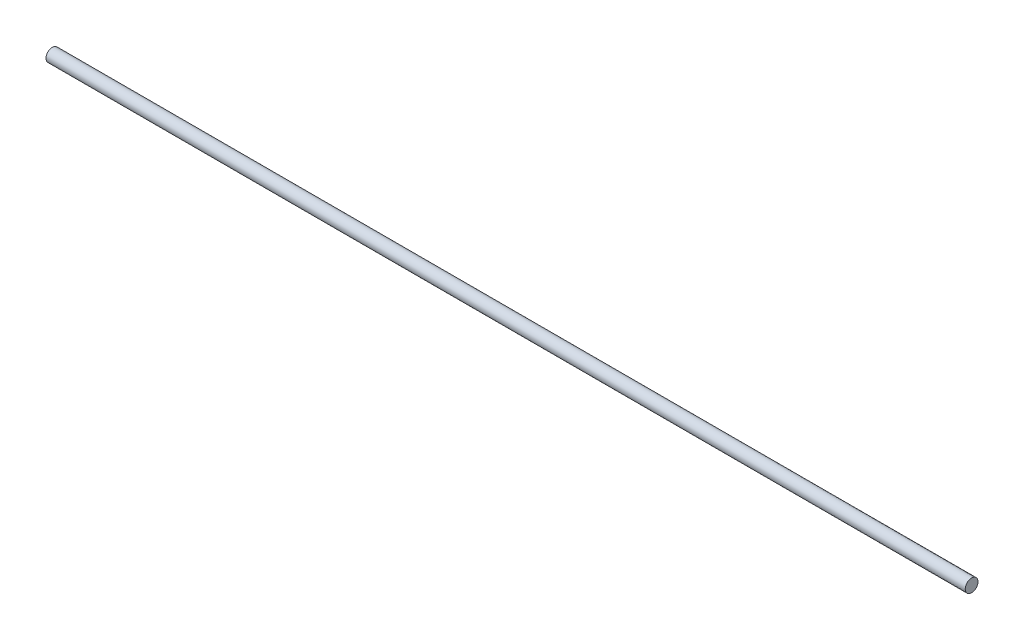
SolidWorks part; units mm, degrees
ref_plane "Front Plane" through (0, 0, 0) normal (0, 0, 1) x (1, 0, 0)
ref_plane "Top Plane" through (0, 0, 0) normal (0, 1, 0) x (1, 0, 0)
ref_plane "Right Plane" through (0, 0, 0) normal (1, 0, 0) x (0, 0, -1)
sketch "Sketch1" plane through (0, 0, 0) normal (1, 0, 0) x (0, 0, -1)
  circle A0 centre (0, 0) radius 6.35
  dimension "D1" = 12.7
extrude "Boss-Extrude1" add sketch "Sketch1" along normal mid plane 914.4
